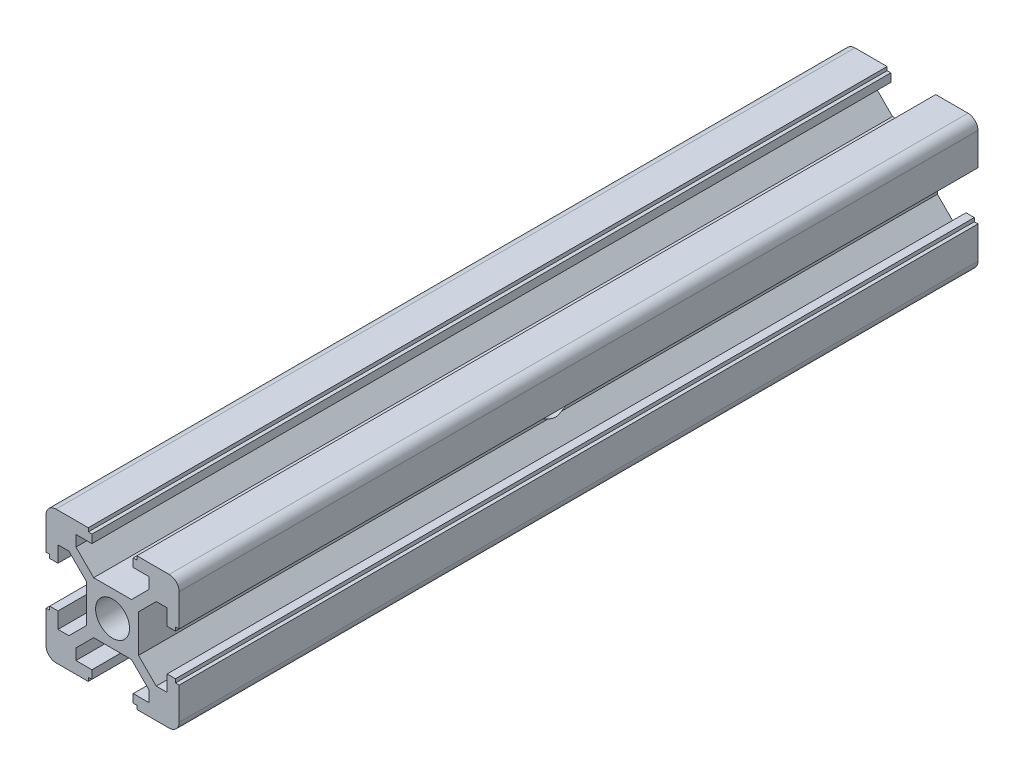
SolidWorks part; units mm, degrees
material "6063-T5"
ref_plane "前视基准面" through (0, 0, 0) normal (0, 0, 1) x (1, 0, 0)
ref_plane "上视基准面" through (0, 0, 0) normal (0, 1, 0) x (1, 0, 0)
ref_plane "右视基准面" through (0, 0, 0) normal (1, 0, 0) x (0, 0, -1)
sketch "草图2" plane through (0, 0, 0) normal (0, 0, 1) x (1, 0, 0)
  line L0 (-3.9, 2.8393) -> (-6.5607, 5.5)
  line L1 (-2.8393, 3.9) -> (2.8393, 3.9)
  line L2 (-3.9, 2.8393) -> (-3.9, -2.8393)
  line L3 (-2.8393, -3.9) -> (2.8393, -3.9)
  line L4 (3.9, 2.8393) -> (3.9, -2.8393)
  line L5 (-3.9, 3.9) -> (3.9, -3.9) construction
  line L6 (-3.9, -3.9) -> (3.9, 3.9) construction
  line L7 (-2.8393, 3.9) -> (-5.5, 6.5607)
  line L8 (-5.5, 6.5607) -> (-5.5, 8.2)
  line L9 (-5.5, 8.2) -> (-3.1, 8.2)
  line L10 (-3.1, 8.2) -> (-3.1, 9.45)
  line L11 (-3.1, 9.45) -> (-3.65, 9.45)
  line L12 (-3.65, 9.45) -> (-3.65, 10)
  line L13 (-3.65, 10) -> (-8.5, 10)
  line L14 (-6.5607, 5.5) -> (-8.2, 5.5)
  line L15 (-10, 3.65) -> (-10, 8.5)
  line L16 (-9.45, 3.65) -> (-10, 3.65)
  line L17 (-9.45, 3.1) -> (-9.45, 3.65)
  line L18 (-8.2, 3.1) -> (-9.45, 3.1)
  line L19 (-8.2, 5.5) -> (-8.2, 3.1)
  line L20 (2.8393, 3.9) -> (5.5, 6.5607)
  line L21 (3.9, 2.8393) -> (6.5607, 5.5)
  line L22 (6.5607, 5.5) -> (8.2, 5.5)
  line L23 (8.2, 5.5) -> (8.2, 3.1)
  line L24 (8.2, 3.1) -> (9.45, 3.1)
  line L25 (9.45, 3.1) -> (9.45, 3.65)
  line L26 (9.45, 3.65) -> (10, 3.65)
  line L27 (10, 3.65) -> (10, 8.5)
  line L28 (5.5, 6.5607) -> (5.5, 8.2)
  line L29 (3.65, 10) -> (8.5, 10)
  line L30 (3.65, 9.45) -> (3.65, 10)
  line L31 (3.1, 9.45) -> (3.65, 9.45)
  line L32 (3.1, 8.2) -> (3.1, 9.45)
  line L33 (5.5, 8.2) -> (3.1, 8.2)
  line L34 (3.9, -2.8393) -> (6.5607, -5.5)
  line L35 (2.8393, -3.9) -> (5.5, -6.5607)
  line L36 (5.5, -6.5607) -> (5.5, -8.2)
  line L37 (5.5, -8.2) -> (3.1, -8.2)
  line L38 (3.1, -8.2) -> (3.1, -9.45)
  line L39 (3.1, -9.45) -> (3.65, -9.45)
  line L40 (3.65, -9.45) -> (3.65, -10)
  line L41 (3.65, -10) -> (8.5, -10)
  line L42 (6.5607, -5.5) -> (8.2, -5.5)
  line L43 (10, -3.65) -> (10, -8.5)
  line L44 (9.45, -3.65) -> (10, -3.65)
  line L45 (9.45, -3.1) -> (9.45, -3.65)
  line L46 (8.2, -3.1) -> (9.45, -3.1)
  line L47 (8.2, -5.5) -> (8.2, -3.1)
  line L48 (-2.8393, -3.9) -> (-5.5, -6.5607)
  line L49 (-3.9, -2.8393) -> (-6.5607, -5.5)
  line L50 (-6.5607, -5.5) -> (-8.2, -5.5)
  line L51 (-8.2, -5.5) -> (-8.2, -3.1)
  line L52 (-8.2, -3.1) -> (-9.45, -3.1)
  line L53 (-9.45, -3.1) -> (-9.45, -3.65)
  line L54 (-9.45, -3.65) -> (-10, -3.65)
  line L55 (-10, -3.65) -> (-10, -8.5)
  line L56 (-5.5, -6.5607) -> (-5.5, -8.2)
  line L57 (-3.65, -10) -> (-8.5, -10)
  line L58 (-3.65, -9.45) -> (-3.65, -10)
  line L59 (-3.1, -9.45) -> (-3.65, -9.45)
  line L60 (-3.1, -8.2) -> (-3.1, -9.45)
  line L61 (-5.5, -8.2) -> (-3.1, -8.2)
  circle A0 centre (0, 0) radius 2.55
  arc A1 (-8.5, 10) -> (-10, 8.5) centre (-8.5, 8.5) ccw
  arc A2 (10, 8.5) -> (8.5, 10) centre (8.5, 8.5) ccw
  arc A3 (8.5, -10) -> (10, -8.5) centre (8.5, -8.5) ccw
  arc A4 (-10, -8.5) -> (-8.5, -10) centre (-8.5, -8.5) ccw
  point P25 (-10, 10)
  point P79 (0, 0)
  dimension "D1" = 5.1
  dimension "D9" = 1.5
  dimension "D2" = 7.8
  dimension "D3" = 1.5
  dimension "D4" = 10
  dimension "D5" = 3.1
  dimension "D6" = 0.55
  dimension "D7" = 1.8
  dimension "D8" = 5.5
  dimension "D11" = 3.9
  dimension "D10" = 4
extrude "凸台-拉伸1" add sketch "草图2" along normal blind 120
sketch "草图3" plane through (10, 0, 0) normal (1, 0, 0) x (0, 0, -1)
  circle A0 centre (-57.5, 0) radius 3
  circle A1 centre (-302.5, 0) radius 3
  dimension "D1" = 6
  dimension "D2" = 6
extrude "切除-拉伸1" cut sketch "草图3" against normal through all
